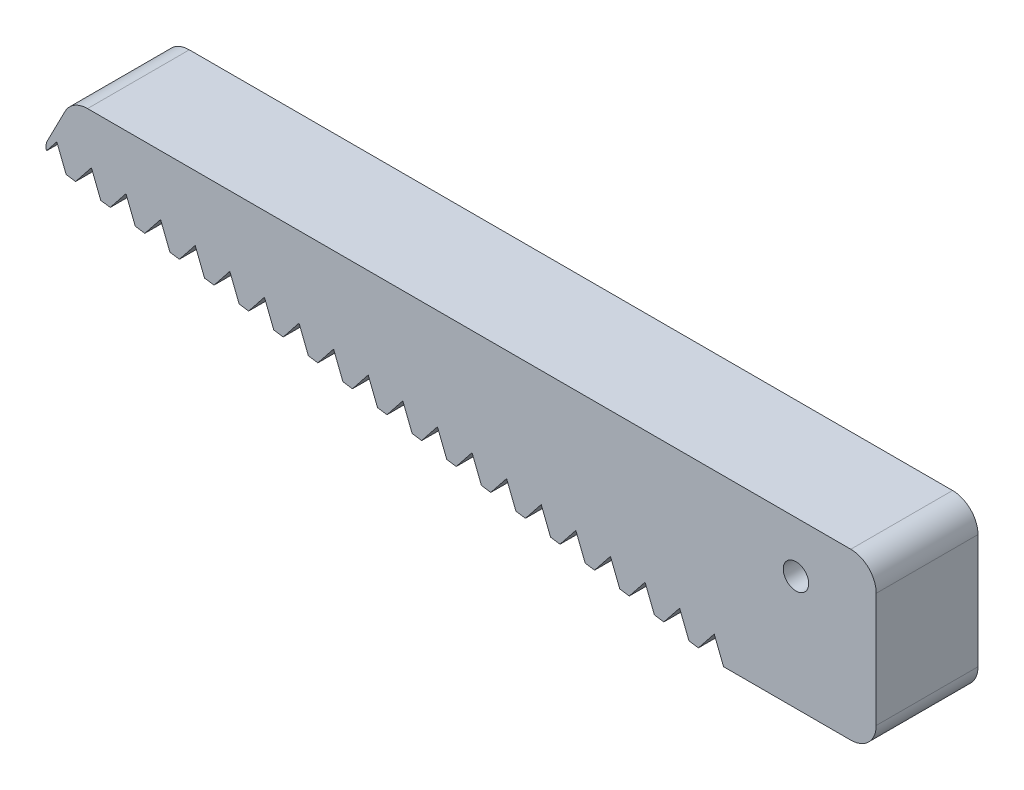
SolidWorks part; units mm, degrees
material "6063-O"
ref_plane "Front" through (0, 0, 0) normal (0, 0, 1) x (1, 0, 0)
ref_plane "Top" through (0, 0, 0) normal (0, 1, 0) x (1, 0, 0)
ref_plane "Right" through (0, 0, 0) normal (1, 0, 0) x (0, 0, -1)
sketch "Sketch1" plane through (0, 0, 0) normal (0, 0, 1) x (1, 0, 0)
  line L1 (-4.4139, 7.7806) -> (48, 0)
  line L2 (48, 0) -> (58, 0)
  line L3 (60, 2) -> (60, 11)
  line L4 (58, 13) -> (-2, 13)
  line L5 (-5.1569, 9.226) -> (-3.7798, 11.9124)
  arc A0 (-3.7798, 11.9124) -> (-2, 13) centre (-2, 11) cw
  arc A1 (60, 11) -> (58, 13) centre (58, 11) ccw
  arc A2 (60, 2) -> (58, 0) centre (58, 2) cw
  arc A3 (-5.1569, 9.226) -> (-4.4139, 7.7806) centre (-4.267, 8.7698) ccw
  circle A4 centre (53.6892, 9) radius 1
  point P10 (60, 13)
  point P13 (60, 0)
  dimension "D1" = 2
  dimension "D2" = 2
  dimension "D4" = 2
  dimension "D5" = 1
  dimension "D8" = 2
  dimension "D9" = 4
  dimension "D3" = 13
  dimension "D6" = 60
  dimension "D7" = 10
extrude "Boss-Extrude1" add sketch "Sketch1" along normal blind 8
sketch "Sketch2" plane through (0, 0, 8) normal (0, 0, 1) x (1, 0, 0)
  line L0 (48, 0) -> (47.2652, 1.8601)
  line L1 (47.2652, 1.8601) -> (46.0217, 0.2937)
  line L2 (-4.4139, 7.7806) -> (48, 0) construction
  line L3 (46.0217, 0.2937) -> (45.2798, 0.4038)
  line L4 (45.2798, 0.4038) -> (44.545, 2.2639)
  line L5 (44.545, 2.2639) -> (43.3015, 0.6975)
  line L6 (48, 0) -> (43.3015, 0.6975)
  line L7 (42.5596, 0.8073) -> (41.8247, 2.6674)
  line L8 (41.8247, 2.6674) -> (40.5812, 1.1009)
  line L9 (39.8394, 1.2111) -> (39.1045, 3.0712)
  line L10 (39.1045, 3.0712) -> (37.8611, 1.5047)
  line L11 (42.5596, 0.8073) -> (37.8611, 1.5047)
  line L12 (37.1191, 1.6145) -> (36.3843, 3.4746)
  line L13 (36.3843, 3.4746) -> (35.1408, 1.9082)
  line L14 (34.3989, 2.0183) -> (33.6641, 3.8784)
  line L15 (33.6641, 3.8784) -> (32.4206, 2.312)
  line L16 (37.1191, 1.6145) -> (32.4206, 2.312)
  line L17 (31.6787, 2.4218) -> (30.9439, 4.2819)
  line L18 (30.9439, 4.2819) -> (29.7004, 2.7154)
  line L19 (28.9585, 2.8256) -> (28.2237, 4.6857)
  line L20 (28.2237, 4.6857) -> (26.9802, 3.1192)
  line L21 (31.6787, 2.4218) -> (26.9802, 3.1192)
  line L22 (26.2383, 3.229) -> (25.5034, 5.0891)
  line L23 (25.5034, 5.0891) -> (24.2599, 3.5227)
  line L24 (23.5181, 3.6328) -> (22.7832, 5.4929)
  line L25 (22.7832, 5.4929) -> (21.5397, 3.9265)
  line L26 (26.2383, 3.229) -> (21.5397, 3.9265)
  line L27 (20.7978, 4.0363) -> (20.063, 5.8964)
  line L28 (20.063, 5.8964) -> (18.8195, 4.3299)
  line L29 (18.0776, 4.4401) -> (17.3428, 6.3002)
  line L30 (17.3428, 6.3002) -> (16.0993, 4.7337)
  line L31 (20.7978, 4.0363) -> (16.0993, 4.7337)
  line L32 (15.3574, 4.8435) -> (14.6226, 6.7036)
  line L33 (14.6226, 6.7036) -> (13.3791, 5.1372)
  line L34 (12.6372, 5.2473) -> (11.9024, 7.1074)
  line L35 (11.9024, 7.1074) -> (10.6589, 5.541)
  line L36 (15.3574, 4.8435) -> (10.6589, 5.541)
  line L37 (9.917, 5.6508) -> (9.1821, 7.5109)
  line L38 (9.1821, 7.5109) -> (7.9386, 5.9445)
  line L39 (7.1968, 6.0546) -> (6.4619, 7.9147)
  line L40 (6.4619, 7.9147) -> (5.2184, 6.3483)
  line L41 (9.917, 5.6508) -> (5.2184, 6.3483)
  line L42 (4.4765, 6.458) -> (3.7417, 8.3182)
  line L43 (3.7417, 8.3182) -> (2.4982, 6.7517)
  line L44 (1.7563, 6.8618) -> (1.0215, 8.722)
  line L45 (1.0215, 8.722) -> (-0.222, 7.1555)
  line L46 (4.4765, 6.458) -> (-0.222, 7.1555)
  line L47 (-0.9639, 7.2653) -> (-1.6988, 9.1254)
  line L48 (-1.6988, 9.1254) -> (-2.9422, 7.559)
  line L49 (-3.6841, 7.6691) -> (-4.4189, 9.5292)
  line L50 (-4.4189, 9.5292) -> (-5.2328, 8.504)
  line L51 (-0.9639, 7.2653) -> (-3.6841, 7.6691)
  line L52 (-3.6841, 7.6691) -> (-4.4139, 7.7806)
  line L53 (-3.6841, 7.6691) -> (-4.3603, 7.7724)
  arc A1 (-5.2328, 8.504) -> (-4.3603, 7.7724) centre (-4.267, 8.7698) ccw
  arc M13 (-5.1569, 9.226) -> (-4.4139, 7.7806) centre (-4.267, 8.7698) ccw
  line M14 (-4.4139, 7.7806) -> (48, 0)
  dimension "D7" = 2.0034
  dimension "D1" = 2
  dimension "D2" = 0.75
  dimension "D3" = 2
  dimension "D4" = 60
  dimension "D5" = 2
  dimension "D6" = 10
extrude "Cut-Extrude1" cut sketch "Sketch2" against normal blind 10 contours L47 L48 M14 | L49 L50 M13 M14 | L44 L45 M14 | L42 L43 M14 | L39 L40 M14 | L37 L38 M14 | L34 L35 M14 | L32 L33 M14 | L29 L30 M14 | L27 L28 M14 | L24 L25 M14 | L22 L23 M14 | L19 L20 M14 | L17 L18 M14 | L0 L1 M14 | L4 L5 M14 | L7 L8 M14 | L9 L10 M14 | L12 L13 M14 | L14 L15 M14
